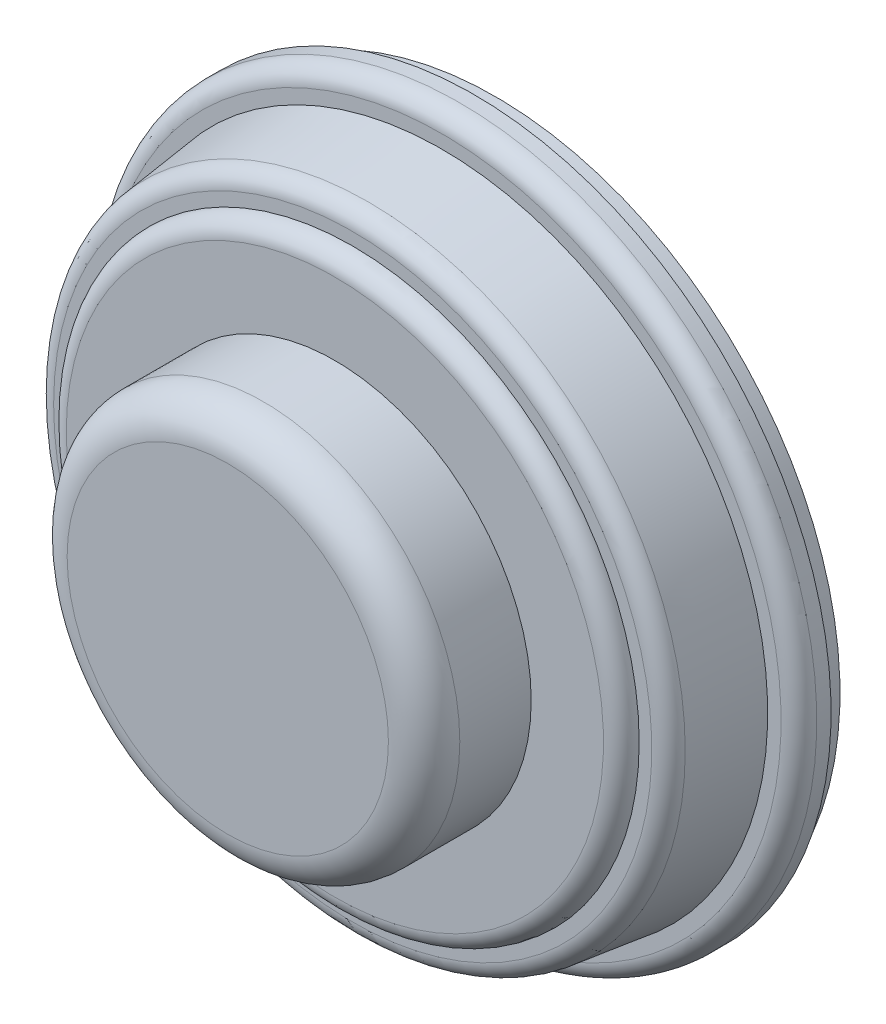
SolidWorks part; units mm, degrees
ref_plane "Front" through (0, 0, 0) normal (0, 0, 1) x (1, 0, 0)
ref_plane "Top" through (0, 0, 0) normal (0, 1, 0) x (1, 0, 0)
ref_plane "Right" through (0, 0, 0) normal (1, 0, 0) x (0, 0, -1)
sketch "Эскиз1" plane through (0, 0, 0) normal (0, 1, 0) x (1, 0, 0)
  line L10 (0, 0) -> (0, -30.0177) construction
  line L11 (0, -0.2) -> (0, -15)
  line L13 (9.5, -2.5) -> (12.5, -2.5)
  line L14 (17.8, -2.5) -> (18.3, -2.5)
  line L15 (18.3, -2.5) -> (18.3, 0)
  line L16 (18.3, 0) -> (19.3, 0)
  line L17 (19.3, 0) -> (19.3, -1.2)
  line L18 (18.25, -3) -> (17.75, -7.1205)
  line L19 (16.7573, -8) -> (16.05, -8)
  line L20 (15.05, -9) -> (11, -9)
  line L21 (11, -9) -> (11, -13)
  line L22 (9, -15) -> (0, -15)
  line L23 (12.8807, -0.5) -> (15.6513, -0.5) construction
  line L24 (19.3, -1.2) -> (20, -1.2)
  line L25 (20, -1.2) -> (20, -2)
  line L26 (19, -3) -> (18.25, -3)
  arc A3 (0, -0.2) -> (9.5, -2.5) centre (0, -20.9696) cw
  arc A6 (17.75, -7.1205) -> (16.7573, -8) centre (16.7573, -7) cw
  arc A7 (16.05, -8) -> (15.05, -9) centre (15.05, -8) cw
  arc A8 (11, -13) -> (9, -15) centre (9, -13) cw
  arc A9 (12.5, -2.5) -> (17.8, -2.5) centre (15.15, -3.2556) cw
  arc A10 (20, -2) -> (19, -3) centre (19, -2) cw
  dimension "D7" = 1
  dimension "D8" = 1
  dimension "D9" = 22
  dimension "D1" = 35.5
  dimension "D5" = 6
  dimension "D10" = 2
  dimension "D16" = 0.5
  dimension "D17" = 40
  dimension "D19" = 1
  dimension "D2" = 38.6
  dimension "D3" = 3
  dimension "D4" = 1.2
  dimension "D6" = 1.7
  dimension "D11" = 15
  dimension "D12" = 19
  dimension "D13" = 0.2
  dimension "D15" = 3
  dimension "D18" = 36.5
  dimension "D20" = 1
  dimension "D21" = 0.5
  dimension "D22" = 2.5
revolve "Повернуть1" add sketch "Эскиз1" angle 360 about L10
